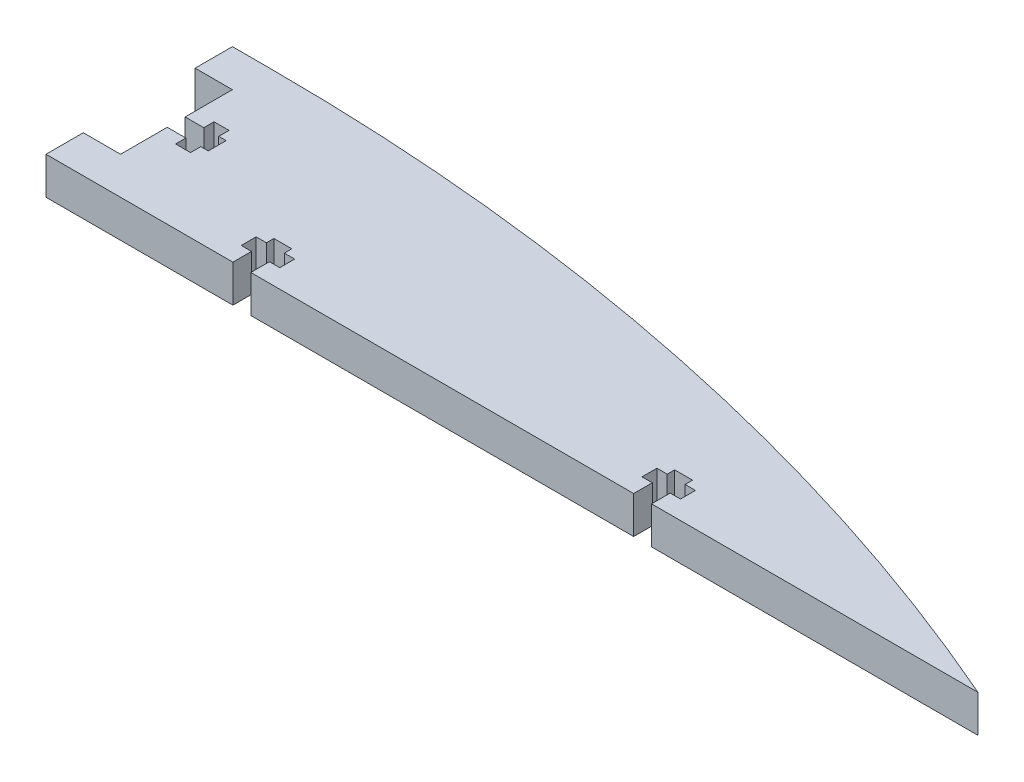
SolidWorks part; units mm, degrees
material "6061 Alloy"
ref_plane "Front Plane" through (0, 0, 0) normal (0, 0, 1) x (1, 0, 0)
ref_plane "Top Plane" through (0, 0, 0) normal (0, 1, 0) x (1, 0, 0)
ref_plane "Right Plane" through (0, 0, 0) normal (1, 0, 0) x (0, 0, -1)
sketch "Sketch1" plane through (0, 0, 0) normal (0, 1, 0) x (1, 0, 0)
  line L0 (-163.1695, 1.1657) -> (-163.1695, -6.8827)
  line L1 (-163.1695, -9.9305) -> (-163.1695, -17.8843)
  line L2 (-10.7695, -24.2343) -> (-66.3745, -24.2343)
  line L3 (-69.4223, -24.2343) -> (-134.637, -24.2343)
  line L4 (-137.6848, -24.2343) -> (-169.5195, -24.2343)
  line L5 (-163.1695, 7.5157) -> (-169.5195, 7.5157)
  line L6 (-156.1845, -6.8827) -> (-157.4545, -6.8827)
  line L7 (-157.4545, -6.8827) -> (-157.4545, -5.1301)
  line L8 (-157.4545, -5.1301) -> (-159.9945, -5.1301)
  line L9 (-159.9945, -5.1301) -> (-159.9945, -6.8827)
  line L10 (-159.9945, -6.8827) -> (-163.1695, -6.8827)
  line L11 (-156.1845, -9.9305) -> (-157.4545, -9.9305)
  line L12 (-157.4545, -9.9305) -> (-157.4545, -11.6831)
  line L13 (-157.4545, -11.6831) -> (-159.9945, -11.6831)
  line L14 (-159.9945, -11.6831) -> (-159.9945, -9.9305)
  line L15 (-159.9945, -9.9305) -> (-163.1695, -9.9305)
  line L16 (-169.5195, 7.5157) -> (-169.5195, 1.1657)
  line L17 (-169.5195, 1.1657) -> (-163.1695, 1.1657)
  line L18 (-169.5195, -24.2343) -> (-169.5195, -17.8843)
  line L19 (-169.5195, -17.8843) -> (-163.1695, -17.8843)
  line L20 (-134.637, -17.2493) -> (-134.637, -18.5193)
  line L21 (-134.637, -18.5193) -> (-132.8844, -18.5193)
  line L22 (-132.8844, -18.5193) -> (-132.8844, -21.0593)
  line L23 (-132.8844, -21.0593) -> (-134.637, -21.0593)
  line L24 (-134.637, -21.0593) -> (-134.637, -24.2343)
  line L25 (-137.6848, -17.2493) -> (-137.6848, -18.5193)
  line L26 (-137.6848, -18.5193) -> (-139.4374, -18.5193)
  line L27 (-139.4374, -18.5193) -> (-139.4374, -21.0593)
  line L28 (-139.4374, -21.0593) -> (-137.6848, -21.0593)
  line L29 (-137.6848, -21.0593) -> (-137.6848, -24.2343)
  line L30 (-66.3745, -17.2493) -> (-66.3745, -18.5193)
  line L31 (-66.3745, -18.5193) -> (-64.6219, -18.5193)
  line L32 (-64.6219, -18.5193) -> (-64.6219, -21.0593)
  line L33 (-64.6219, -21.0593) -> (-66.3745, -21.0593)
  line L34 (-66.3745, -21.0593) -> (-66.3745, -24.2343)
  line L35 (-69.4223, -17.2493) -> (-69.4223, -18.5193)
  line L36 (-69.4223, -18.5193) -> (-71.1749, -18.5193)
  line L37 (-71.1749, -18.5193) -> (-71.1749, -21.0593)
  line L38 (-71.1749, -21.0593) -> (-69.4223, -21.0593)
  line L39 (-69.4223, -21.0593) -> (-69.4223, -24.2343)
  line L40 (-156.1845, -6.8827) -> (-156.1845, -9.9305)
  line L41 (-137.6848, -17.2493) -> (-134.637, -17.2493)
  line L42 (-69.4223, -17.2493) -> (-66.3745, -17.2493)
  arc A0 (-10.7695, -24.2343) -> (-163.1695, 7.5157) centre (-163.1695, -374.1193) ccw
extrude "Boss-Extrude1" add sketch "Sketch1" along normal blind 6.35
